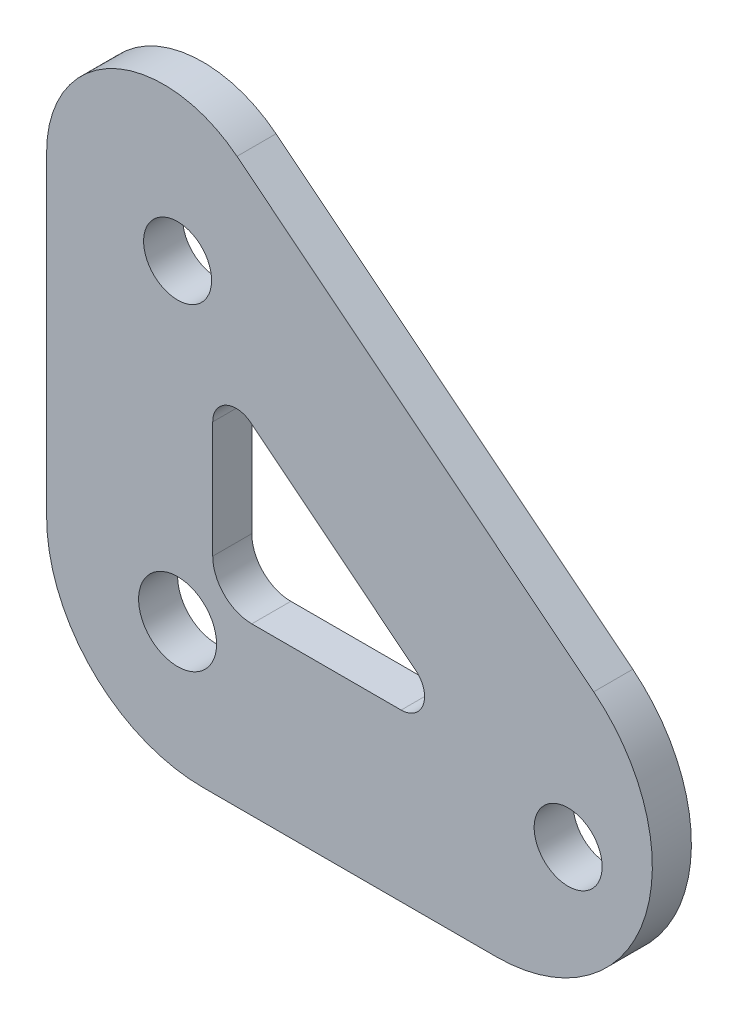
SolidWorks part; units mm, degrees
ref_plane "Front Plane" through (0, 0, 0) normal (0, 0, 1) x (1, 0, 0)
ref_plane "Top Plane" through (0, 0, 0) normal (0, 1, 0) x (1, 0, 0)
ref_plane "Right Plane" through (0, 0, 0) normal (1, 0, 0) x (0, 0, -1)
sketch "Sketch1" plane through (0, 0, 0) normal (0, 0, 1) x (1, 0, 0)
  line L0 (0, 91.6485) -> (0, 0)
  line L1 (0, 0) -> (114.5606, 0)
  line L2 (114.5606, 0) -> (0, 91.6485)
  line L3 (0, 91.6485) -> (29.75, 29.75) construction
  line L4 (29.75, 29.75) -> (0, 0) construction
  line L5 (29.75, 29.75) -> (114.5606, 0) construction
  line L6 (16.7656, 56.7656) -> (16.7656, 16.7656) construction
  line L7 (16.7656, 16.7656) -> (66.7656, 16.7656) construction
  line L8 (66.7656, 16.7656) -> (16.7656, 56.7656) construction
  circle A0 centre (16.7656, 56.7656) radius 4.35
  circle A1 centre (29.75, 29.75) radius 29.75 construction
  circle A2 centre (66.7656, 16.7656) radius 4.35
  circle A3 centre (16.7656, 16.7656) radius 4.99
  dimension "D1" = 8.7
  dimension "D2" = 9.98
  dimension "D3" = 8.7
  dimension "D4" = 50
  dimension "D5" = 40
extrude "Boss-Extrude1" add sketch "Sketch1" along normal blind 5
fillet "Fillet1" radius 15 1 edges at (0, 91.6485, 2.5)
fillet "Fillet2" radius 20 1 edges at (0, 0, 2.5)
fillet "Fillet3" radius 20 1 edges at (114.5606, 0, 2.5)
sketch "Sketch2" plane through (0, 0, 5) normal (0, 0, 1) x (1, 0, 0)
  line L0 (16.7656, 56.7656) -> (16.7656, 16.7656) construction
  line L1 (16.7656, 16.7656) -> (66.7656, 16.7656) construction
  line L2 (66.7656, 16.7656) -> (16.7656, 56.7656) construction
  line L3 (21.2656, 47.4028) -> (53.9371, 21.2656)
  line L4 (53.9371, 21.2656) -> (21.2656, 21.2656)
  line L5 (21.2656, 21.2656) -> (21.2656, 47.4028)
  dimension "D1" = 4.5
  dimension "D2" = 4.5
  dimension "D3" = 9
extrude "Cut-Extrude1" cut sketch "Sketch2" against normal through all
fillet "Fillet4" radius 5 1 edges at (21.2656, 21.2656, 2.5)
fillet "Fillet5" radius 3 1 edges at (21.2656, 47.4028, 2.5)
fillet "Fillet6" radius 3 1 edges at (53.9371, 21.2656, 2.5)
